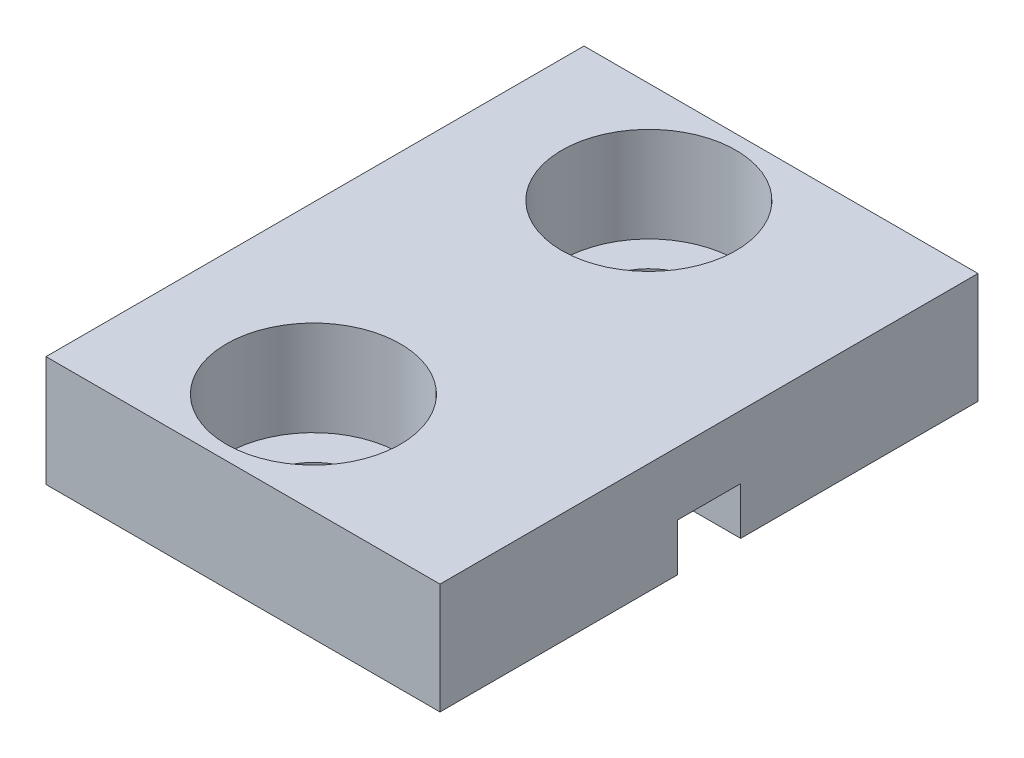
SolidWorks part; units mm, degrees
ref_plane "Alzado" through (0, 0, 0) normal (0, 0, 1) x (1, 0, 0)
ref_plane "Planta" through (0, 0, 0) normal (0, 1, 0) x (1, 0, 0)
ref_plane "Vista lateral" through (0, 0, 0) normal (1, 0, 0) x (0, 0, -1)
sketch "Croquis1" plane through (0, 0, 0) normal (0, 1, 0) x (1, 0, 0)
  line L0 (5.25, 17) -> (5.25, 13.8) construction
  line L1 (0, 0) -> (10.5, 0)
  line L2 (0, 0) -> (0, 17)
  line L3 (0, 17) -> (10.5, 17)
  line L4 (10.5, 0) -> (10.5, 17)
  line L5 (10.5, 8.5) -> (0, 8.5) construction
  circle A0 centre (5.25, 13.8) radius 1.6
  circle A1 centre (5.25, 3.2) radius 1.6
  dimension "D3" = 3.2
  dimension "D1" = 10.5
  dimension "D2" = 17
  dimension "D4" = 3.2
extrude "Saliente-Extruir1" add sketch "Croquis1" along normal blind 3.5
sketch "Croquis2" plane through (0, 3.5, 0) normal (0, 1, 0) x (1, 0, 0)
  circle A0 centre (5.25, 13.8) radius 2.75
  circle A1 centre (5.25, 3.2) radius 2.75
  dimension "D1" = 5.5
extrude "Cortar-Extruir1" cut sketch "Croquis2" against normal blind 3
sketch "Croquis3" plane through (10.5, 0, 0) normal (1, 0, 0) x (0, 0, -1)
  line L0 (0, 0) -> (17, 0) construction
  line L1 (7.5, 0) -> (9.5, 0)
  line L2 (7.5, 0) -> (7.5, 0.5)
  line L3 (7.5, 0.5) -> (9.5, 0.5)
  line L4 (9.5, 0) -> (9.5, 0.5)
  line L5 (8.5, 0.5) -> (8.5, 3.5) construction
  line L6 (0, 3.5) -> (17, 3.5) construction
  dimension "D1" = 0.5
  dimension "D2" = 2
extrude "Cortar-Extruir2" cut sketch "Croquis3" against normal blind 16
sketch "Croquis4" plane through (0, 0.5, 0) normal (0, -1, 0) x (1, 0, 0)
  line L0 (0, -7.5) -> (10.5, -7.5) construction
  line L1 (10.5, -9.5) -> (7.5, -9.5)
  line L2 (10.5, -9.5) -> (10.5, -7.5)
  line L3 (10.5, -7.5) -> (7.5, -7.5)
  line L4 (7.5, -9.5) -> (7.5, -7.5)
  dimension "D1" = 3
extrude "Cortar-Extruir3" cut sketch "Croquis4" against normal blind 1
sketch "Croquis5" plane through (10.5, 0, 0) normal (1, 0, 0) x (0, 0, -1)
  line L8 (7.5, 1.5) -> (9.5, 1.5)
  line L9 (9.5, 1.5) -> (9.5, 0)
  line L10 (9.5, 0) -> (17, 0)
  line L11 (17, 0) -> (17, 3.5)
  line L12 (17, 3.5) -> (0, 3.5)
  line L13 (0, 3.5) -> (0, 0)
  line L14 (0, 0) -> (7.5, 0)
  line L15 (7.5, 0) -> (7.5, 1.5)
  line L16 (7.5, 1.5) -> (9.5, 1.5)
  line L17 (9.5, 1.5) -> (9.5, 0)
  line L18 (9.5, 0) -> (17, 0)
  line L19 (17, 0) -> (17, 3.5)
  line L20 (17, 3.5) -> (0, 3.5)
  line L21 (0, 3.5) -> (0, 0)
  line L22 (0, 0) -> (7.5, 0)
  line L23 (7.5, 0) -> (7.5, 1.5)
  dimension "D1" = 0
extrude "Saliente-Extruir2" add sketch "Croquis5" along normal blind 10
sketch "Croquis6" plane through (0, 3.5, 0) normal (0, 1, 0) x (1, 0, 0)
  line L0 (20.5, 17) -> (0, 17) construction
  line L1 (20.5, 0) -> (12.45, 0)
  line L2 (20.5, 0) -> (20.5, 17)
  line L3 (20.5, 17) -> (12.45, 17)
  line L4 (12.45, 0) -> (12.45, 17)
  circle A0 centre (5.25, 13.8) radius 2.75 construction
  dimension "D1" = 7.2
extrude "Cortar-Extruir4" cut sketch "Croquis6" against normal blind 10
